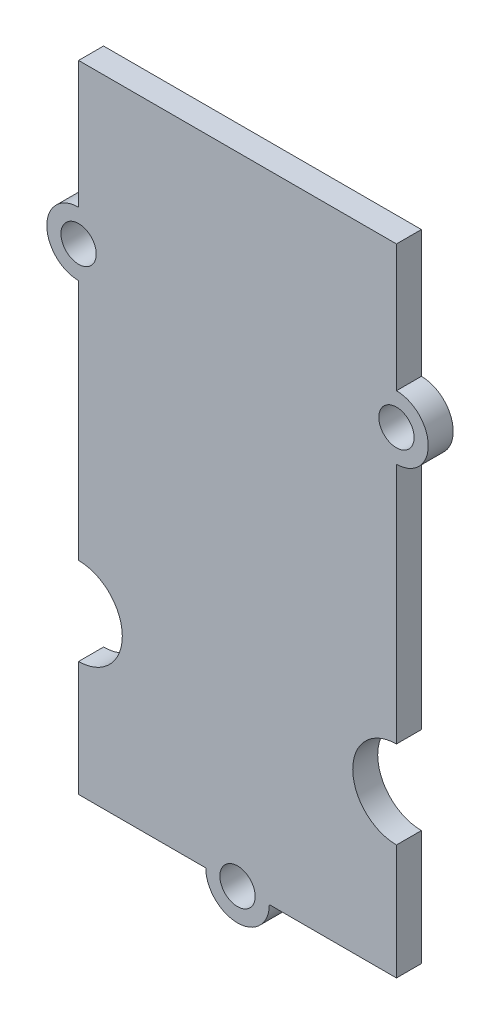
SolidWorks part; units mm, degrees
ref_plane "Front Plane" through (0, 0, 0) normal (0, 0, 1) x (1, 0, 0)
ref_plane "Top Plane" through (0, 0, 0) normal (0, 1, 0) x (1, 0, 0)
ref_plane "Right Plane" through (0, 0, 0) normal (1, 0, 0) x (0, 0, -1)
sketch "Sketch1" plane through (0, 0, 0) normal (0, 0, 1) x (1, 0, 0)
  line L0 (10, 40) -> (10, 0) construction
  line L1 (0, 0) -> (20, 0)
  line L2 (0, 0) -> (0, 40)
  line L3 (0, 40) -> (20, 40)
  line L4 (20, 0) -> (20, 40)
  circle A0 centre (20, 30) radius 1.11
  circle A1 centre (20, 30) radius 2
  circle A2 centre (20, 10) radius 2.75
  circle A3 centre (0, 10) radius 2.75
  circle A4 centre (0, 30) radius 1.11
  circle A5 centre (0, 30) radius 2
  circle A6 centre (10, 0) radius 1.11
  circle A7 centre (10, 0) radius 2
  point P20 (10.3235, 0)
  dimension "D3" = 4
  dimension "D4" = 2.22
  dimension "D6" = 5.5
  dimension "D1" = 20
  dimension "D2" = 40
  dimension "D5" = 10
  dimension "D7" = 10
extrude "Boss-Extrude1" add sketch "Sketch1" along normal blind 1.57 contours L0 L3 L2 A5 A3 L1 A7 | L3 L0 A7 L1 L4 A2 A1 | A5 L2 A4 | A5 L2 A4 | L4 A1 A0 | L4 A1 A0 | A7 L1 A6 | A7 L0 A6 L1 | L0 A7 L1 A6
sketch "Sketch2" plane through (0, 0, 0) normal (0, 0, -1) x (-1, 0, 0)
  line L1 (-12.0205, 7.9795) -> (-7.9795, 7.9795)
  line L2 (-12.0205, 7.9795) -> (-12.0205, 12.0205)
  line L3 (-12.0205, 12.0205) -> (-7.9795, 12.0205)
  line L4 (-7.9795, 7.9795) -> (-7.9795, 12.0205)
  line L5 (-12.0205, 7.9795) -> (-7.9795, 12.0205) construction
  line L6 (-12.0205, 12.0205) -> (-7.9795, 7.9795) construction
  arc A0 (-20, 7.25) -> (-20, 12.75) centre (-20, 10) ccw construction
  arc A1 (-12, 0) -> (-8, 0) centre (-10, 0) ccw construction
  point P0 (-10, 10)
  point P8 (-17.25, 10)
  point P12 (-10, -2)
  point P13 (-12.0205, 12.0205)
extrude "Boss-Extrude2" add sketch "Sketch2" along normal blind 1.57
